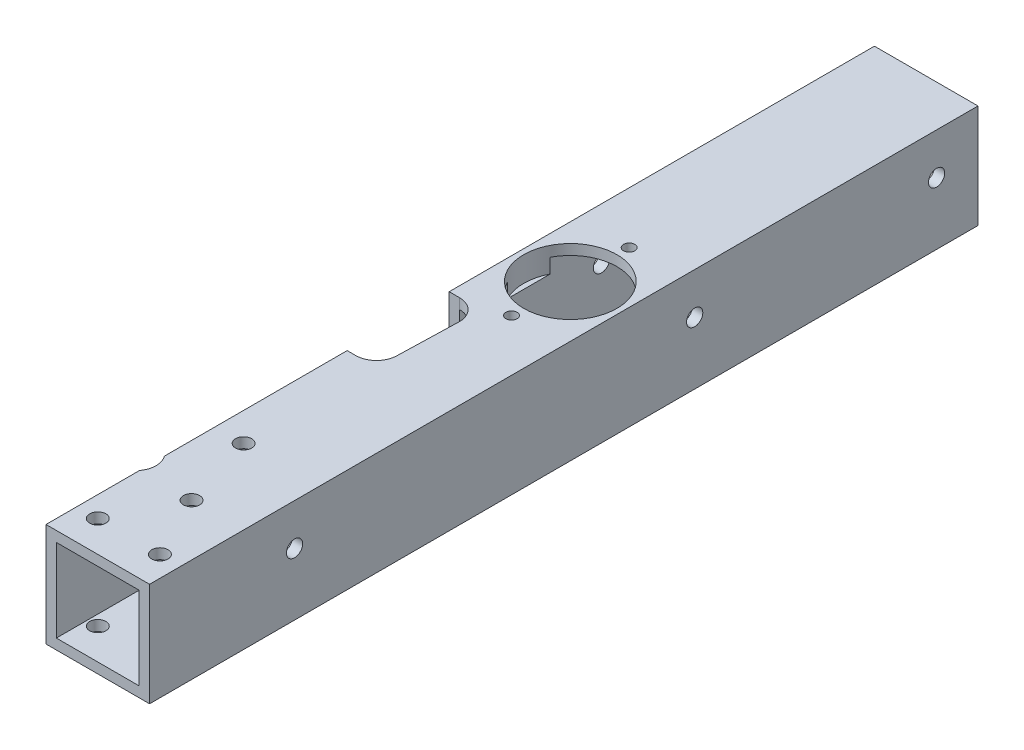
SolidWorks part; units mm, degrees
material "6061 Alloy"
ref_plane "Front Plane" through (0, 0, 0) normal (0, 0, 1) x (1, 0, 0)
ref_plane "Top Plane" through (0, 0, 0) normal (0, 1, 0) x (1, 0, 0)
ref_plane "Right Plane" through (0, 0, 0) normal (1, 0, 0) x (0, 0, -1)
sketch "Sketch1" plane through (0, 0, 0) normal (0, 0, 1) x (1, 0, 0)
  line L0 (-12.7, 12.7) -> (12.7, 12.7)
  line L2 (-15.875, 15.875) -> (15.875, 15.875)
  line L3 (-15.875, 15.875) -> (-15.875, -15.875)
  line L4 (-15.875, -15.875) -> (15.875, -15.875)
  line L5 (15.875, 15.875) -> (15.875, -15.875)
  line L10 (12.7, 12.7) -> (12.7, -12.7)
  line L11 (-12.7, -12.7) -> (12.7, -12.7)
  line L12 (-12.7, 12.7) -> (-12.7, -12.7)
  point P12 (0, 15.875)
  point P14 (15.875, 0)
  dimension "Wall Thickness" = 3.175
  dimension "Outside Width" = 31.75
  dimension "Outside Height" = 31.75
  dimension "Inside Height" = 25.4
  dimension "Inside Width" = 25.4
sketch "Sketch2" plane through (0, 0, 0) normal (1, 0, 0) x (0, 0, -1)
  line L0 (127, 0) -> (-127, 0)
  point P4 (0, 0)
  point P7 (-127, 0)
  point P10 (127, 0)
  dimension "Length" = 254
sketch "Sketch3" plane through (0, 0, 0) normal (0, 0, 1) x (1, 0, 0)
  line L21 (15.875, 15.875) -> (-15.875, 15.875)
  line L22 (15.875, -15.875) -> (15.875, 15.875)
  line L23 (-15.875, -15.875) -> (15.875, -15.875)
  line L24 (-15.875, 15.875) -> (-15.875, -15.875)
  line L25 (15.875, 15.875) -> (-15.875, 15.875)
  line L26 (15.875, -15.875) -> (15.875, 15.875)
  line L27 (-15.875, -15.875) -> (15.875, -15.875)
  line L28 (-15.875, 15.875) -> (-15.875, -15.875)
  line L29 (12.7, 12.7) -> (-12.7, 12.7)
  line L30 (12.7, -12.7) -> (12.7, 12.7)
  line L31 (-12.7, -12.7) -> (12.7, -12.7)
  line L32 (-12.7, 12.7) -> (-12.7, -12.7)
  line L33 (12.7, 12.7) -> (-12.7, 12.7)
  line L34 (12.7, -12.7) -> (12.7, 12.7)
  line L35 (-12.7, -12.7) -> (12.7, -12.7)
  line L36 (-12.7, 12.7) -> (-12.7, -12.7)
  dimension "D1" = 0
  dimension "D2" = 0
extrude "Boss-Extrude1" add sketch "Sketch3" along normal up to vertex (127 mm away) and the other way up to vertex (127 mm away) up to point (0, 0, 127) other way up to point (0, 0, -127)
sketch "Drawing Reference" plane through (0, 0, 0) normal (1, 0, 0) x (0, 0, -1)
  line L0 (-127, 0) -> (127, 0) construction
  line L1 (0, -15.875) -> (0, 15.875) construction
  line L2 (-127, -15.875) -> (127, -15.875) construction
  line L5 (-127, 15.875) -> (127, 15.875) construction
  point P7 (-104.14, 0)
  point P8 (104.14, 0)
  dimension "D1" = 22.86
sketch "Sketch4" plane through (0, 15.875, 0) normal (0, 1, 0) x (1, 0, 0)
  line L0 (0, -127) -> (0, -117.475) construction
  line L1 (15.875, -127) -> (-15.875, -127) construction
  line L2 (0, -117.475) -> (9.525, -117.475) construction
  line L3 (0, -117.475) -> (-9.525, -117.475) construction
  line L4 (0, -117.475) -> (0, 17.8816) construction
  line L5 (0, -117.475) -> (0, -98.2472) construction
  point P5 (-7.1119, -75.1713)
  dimension "D1" = 135.3566
  dimension "D2" = 19.05
  dimension "D3" = 9.525
hole_wizard "#10 Clearance Hole1" positions "Sketch5" profile "Sketch6" hole size "#10" standard "ANSI Inch" end condition through all
sketch "Sketch5" plane through (0, 15.875, 0) normal (0, 1, 0) x (1, 0, 0)
  point P0 (-9.525, -117.475)
  point P3 (9.525, -117.475)
  point P7 (0, -98.2472)
  point P10 (-7.1119, -75.1713)
sketch "Sketch6" plane through (-9.525, 15.875, 117.475) normal (1, 0, 0) x (0, 0, 1)
  line L0 (0, 0) -> (0, 31.75)
  line L1 (0, 31.75) -> (2.4892, 31.75)
  line L2 (2.4892, 31.75) -> (2.4892, 0)
  line L5 (2.4892, 0) -> (0, 0)
  line L11 (0, -6.35) -> (0, 107.95) construction
  dimension "Thru Hole Dia." = 4.9784
  dimension "Thru Hole Depth" = 31.75
sketch "Sketch7" plane through (0, 15.875, 0) normal (0, 1, 0) x (1, 0, 0)
  circle A0 centre (0, 17.8816) radius 14.2875
  dimension "D1" = 28.575
extrude "Cut-Extrude1" cut sketch "Sketch7" against normal blind 7.62
sketch "Sketch8" plane through (0, -15.875, 0) normal (0, -1, 0) x (1, 0, 0)
  circle A0 centre (0, -17.8816) radius 14.2875
  dimension "D1" = 28.575
extrude "Cut-Extrude2" cut sketch "Sketch8" against normal blind 7.62
sketch "Sketch9" plane through (0, -15.875, 0) normal (0, -1, 0) x (1, 0, 0)
  line L0 (-20.5727, 87.7258) -> (-42.1132, 74.2659) construction
  line L1 (-42.1132, 74.2659) -> (-15.875, 32.276) construction
  line L2 (-15.875, 127) -> (-15.875, -127) construction
  line L3 (-15.875, 34.6634) -> (-15.875, 3.3835)
  line L4 (-13.2332, 34.6634) -> (-15.875, 34.6634)
  line L10 (-6.8832, 28.3134) -> (-6.35, 9.7335)
  line L11 (-12.7, 3.3835) -> (-15.875, 3.3835)
  circle A0 centre (-13.2332, 28.3134) radius 6.35 construction
  circle A1 centre (-12.7, 9.7335) radius 6.35 construction
  arc A4 (-6.35, 9.7335) -> (-12.7, 3.3835) centre (-12.7, 9.7335) cw
  arc A5 (-6.8832, 28.3134) -> (-13.2332, 34.6634) centre (-13.2332, 28.3134) ccw
  dimension "D2" = 4.7625
extrude "Cut-Extrude3" cut sketch "Sketch9" against normal through all
sketch "Sketch10" plane through (15.875, 0, 0) normal (1, 0, 0) x (0, 0, -1)
  line L0 (-127, 3.175) -> (-82.55, 3.175) construction
  line L2 (-82.55, 3.175) -> (114.3, 3.175) construction
  line L3 (-127, -15.875) -> (-127, 3.175) construction
  line L4 (52.832, 3.175) -> (40.132, 3.175) construction
  line L5 (52.832, 434.0225) -> (52.832, -10.4775) construction
  dimension "D1" = 44.45
  dimension "D2" = 19.05
  dimension "D3" = 12.7
hole_wizard "#10 Clearance Hole2" positions "Sketch11" profile "Sketch12" hole size "#10" standard "ANSI Inch" end condition through all
sketch "Sketch11" plane through (15.875, 0, 0) normal (1, 0, 0) x (0, 0, -1)
  point P4 (-82.55, 3.175)
  point P7 (114.3, 3.175)
  point P12 (40.132, 3.175)
sketch "Sketch12" plane through (15.875, 3.175, 82.55) normal (0, 1, 0) x (0, 0, -1)
  line L0 (0, 0) -> (0, 31.75)
  line L1 (0, 31.75) -> (2.4892, 31.75)
  line L2 (2.4892, 31.75) -> (2.4892, 0)
  line L5 (2.4892, 0) -> (0, 0)
  line L11 (0, -6.35) -> (0, 107.95) construction
  dimension "Thru Hole Dia." = 4.9784
  dimension "Thru Hole Depth" = 31.75
sketch "Sketch13" plane through (0, -15.875, 0) normal (0, -1, 0) x (1, 0, 0)
  line L0 (-20.955, 94.5257) -> (-15.875, 94.5257) construction
  line L4 (-15.875, 127) -> (-15.875, 34.6634) construction
  circle A1 centre (-20.955, 94.5257) radius 6.35
  dimension "D1" = 5.08
extrude "Cut-Extrude4" cut sketch "Sketch13" against normal through all
sketch "Sketch14" plane through (0, -15.875, 0) normal (0, -1, 0) x (1, 0, 0)
  line L0 (0, -35.9156) -> (0, 0.1524) construction
  line L1 (0, 117.475) -> (0, -17.8816) construction
  line L2 (0, -17.8816) -> (5.4169, -17.8816) construction
  point P7 (0, -17.8816)
  dimension "D1" = 36.068
hole_wizard "Tap Drill for #8-32 Tap1" positions "Sketch17" profile "Sketch18" hole size "#8-32" standard "ANSI Inch"
sketch "Sketch17" plane through (0, 15.875, 0) normal (0, 1, 0) x (1, 0, 0)
  point P4 (0, 35.9156)
  point P9 (0, -0.1524)
sketch "Sketch18" plane through (0, 15.875, -35.9156) normal (1, 0, 0) x (0, 0, 1)
  line L0 (0, 0) -> (0, 6.1178)
  line L1 (0, 6.1178) -> (1.7272, 5.08)
  line L2 (1.7272, 5.08) -> (1.7272, 0)
  line L5 (1.7272, 0) -> (0, 0)
  line L10 (0, 6.1178) -> (-1.7272, 5.08) construction
  line L11 (0, -6.35) -> (0, 107.95) construction
  dimension "Hole Dia." = 3.4544
  dimension "Hole Depth" = 5.08
  dimension "Drill Angle" = 118
equation "\"D1@Drawing Reference\"=\"Outside Width@Sketch1\" * 0.72"
